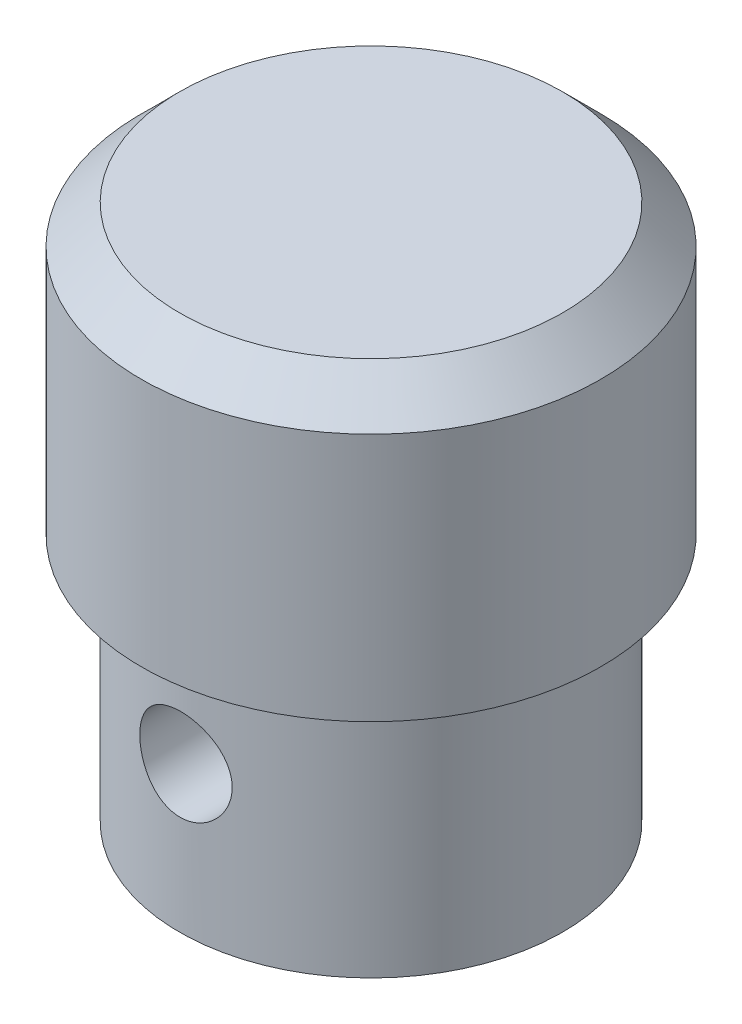
SolidWorks part; units mm, degrees
material "Ottone"
ref_plane "Piano frontale" through (0, 0, 0) normal (0, 0, 1) x (1, 0, 0)
ref_plane "Piano superiore" through (0, 0, 0) normal (0, 1, 0) x (1, 0, 0)
ref_plane "Piano destro" through (0, 0, 0) normal (1, 0, 0) x (0, 0, -1)
sketch "Schizzo1" plane through (0, 0, 0) normal (0, 0, 1) x (1, 0, 0)
  line L0 (-6, 14) -> (-6, 6.5)
  line L1 (-6, 6.5) -> (-5, 6.5)
  line L2 (-5, 6.5) -> (-5, 0)
  line L3 (-5, 0) -> (0, 0)
  line L4 (0, 0) -> (0, 14)
  line L5 (0, 14) -> (-6, 14)
  line L6 (0, 0) -> (0, 21.5243) construction
  dimension "D1" = 14
  dimension "D2" = 7.5
  dimension "D3" = 12
  dimension "D4" = 10
revolve "Rivoluzione1" add sketch "Schizzo1" angle 360 about L6
chamfer "Smusso1" distance 1 angle 45 1 edges at (0, 14, -6)
sketch "Schizzo2" plane through (0, 0, 0) normal (0, -1, 0) x (-1, 0, 0)
  circle A0 centre (0, 0) radius 1.5
  dimension "D1" = 3
extrude "Taglio-Estrusione1" cut sketch "Schizzo2" against normal blind 10
hole_wizard "Foro per Vite M2-2" positions "Schizzo3D2" profile "Schizzo4" hole size "M2" standard "ISO"
sketch3d "Schizzo3D2"
  line L0 (0, 0, 0) -> (0, 14.2556, 0) construction
  point P0 (0.0236, 3.8057, 4.9999)
sketch "Schizzo4" plane through (0.0236, 3.8057, 4.9999) normal (0, 1, 0) x (1, 0, -0.0047)
  line L0 (0, 0) -> (0, 3.5)
  line L1 (0, 3.5) -> (1.2, 3.5)
  line L2 (1.2, 3.5) -> (1.2, 0)
  line L5 (1.2, 0) -> (0, 0)
  line L11 (0, -6.35) -> (0, 107.95) construction
  dimension "Thru Hole Dia." = 2.4
  dimension "Thru Hole Depth" = 3.5
